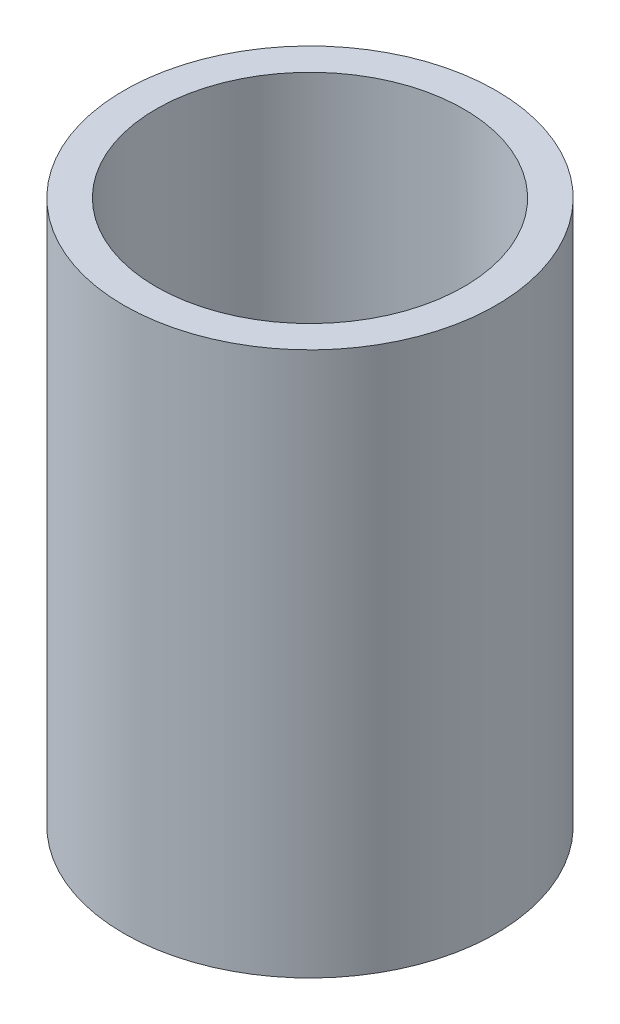
SolidWorks part; units mm, degrees
ref_plane "Front Plane" through (0, 0, 0) normal (0, 0, 1) x (1, 0, 0)
ref_plane "Top Plane" through (0, 0, 0) normal (0, 1, 0) x (1, 0, 0)
ref_plane "Right Plane" through (0, 0, 0) normal (1, 0, 0) x (0, 0, -1)
sketch "Sketch1" plane through (0.1219, -28.8626, 6.4001) normal (0, 1, 0) x (1, 0, 0)
  circle A0 centre (-0.1219, 6.4001) radius 6.5
  circle A1 centre (-0.1219, 6.4001) radius 5.375
  dimension "D1" = 13
  dimension "D2" = 10.75
extrude "Boss-Extrude1" add sketch "Sketch1" along normal blind 19
